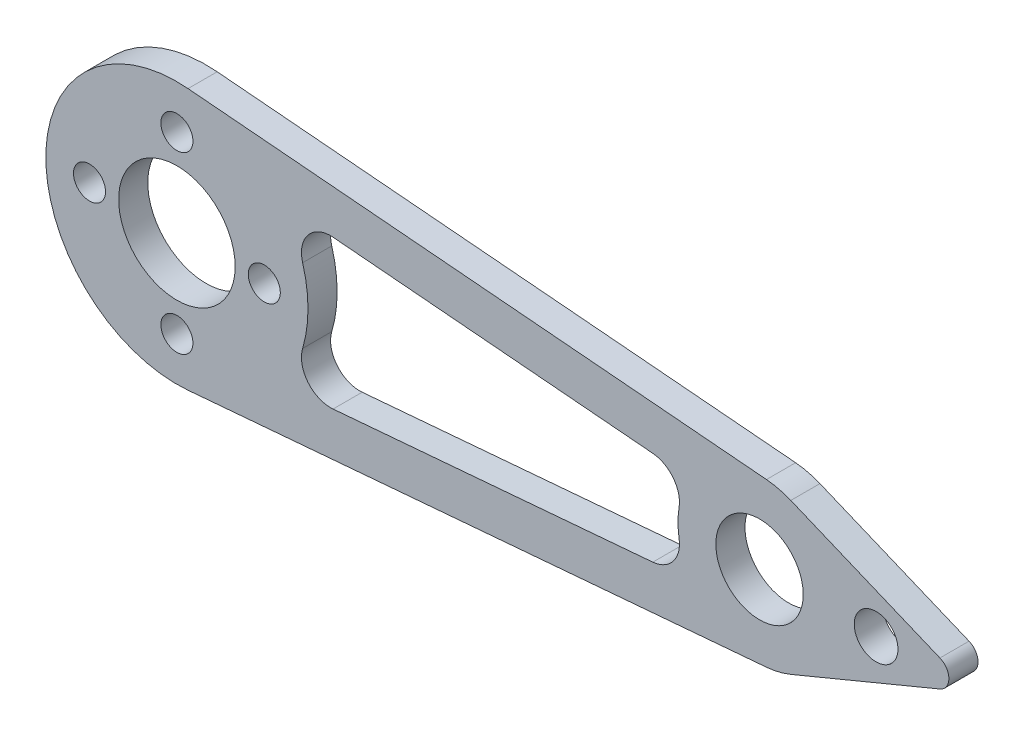
SolidWorks part; units mm, degrees
ref_plane "Plan de face" through (0, 0, 0) normal (0, 0, 1) x (1, 0, 0)
ref_plane "Plan de dessus" through (0, 0, 0) normal (0, 1, 0) x (1, 0, 0)
ref_plane "Plan de droite" through (0, 0, 0) normal (1, 0, 0) x (0, 0, -1)
sketch "Esquisse1" plane through (0, 0, 0) normal (0, 0, 1) x (1, 0, 0)
  circle A0 centre (0, 0) radius 6 construction
  circle A1 centre (0, 6) radius 1.1
  circle A2 centre (6, 0) radius 1.1
  circle A3 centre (0, -6) radius 1.1
  circle A4 centre (-6, 0) radius 1.1
  circle A5 centre (0, 0) radius 4
  circle A6 centre (0, 0) radius 9
  point P14 (0, 0)
  dimension "D1" = 12
  dimension "D2" = 2.2
  dimension "D4" = 2
  dimension "D5" = 3
  dimension "D3" = 4
extrude "Boss.-Extru.1" add sketch "Esquisse1" along normal blind 2
sketch "Esquisse2" plane through (0, 0, 2) normal (0, 0, 1) x (1, 0, 0)
  line L0 (0, 0) -> (40, 0) construction
  line L1 (0.765, 8.9674) -> (40.476, 5.5797)
  line L2 (0.765, -8.9674) -> (40.476, -5.5797)
  circle A0 centre (40, 0) radius 3
  arc A1 (40.476, -5.5797) -> (40.476, 5.5797) centre (40, 0) ccw
  circle A2 centre (0, 0) radius 9 construction
  arc A3 (0.765, -8.9674) -> (0.765, 8.9674) centre (0, 0) ccw
  dimension "D1" = 6
  dimension "D2" = 2.6
  dimension "D3" = 40
extrude "Boss.-Extru.2" add sketch "Esquisse2" against normal blind 2
sketch "Esquisse3" plane through (0, 0, 2) normal (0, 0, 1) x (1, 0, 0)
  line L0 (7.1939, 5.4081) -> (35.2791, 3.0122)
  line L1 (40.476, 5.5797) -> (0.765, 8.9674) construction
  line L2 (0, 0) -> (40, 0) construction
  line L3 (7.1939, -5.4081) -> (35.2791, -3.0122)
  arc A0 (7.1939, -5.4081) -> (7.1939, 5.4081) centre (0, 0) ccw
  arc A1 (35.2791, 3.0122) -> (35.2791, -3.0122) centre (40, 0) ccw
  dimension "D1" = 3
extrude "Enlèv. mat.-Extru.1" cut sketch "Esquisse3" against normal through all
fillet "Congé1" radius 2 4 edges at (35.2791, -3.0122, 1) (35.2791, 3.0122, 1) (7.1939, -5.4081, 1) (7.1939, 5.4081, 1)
sketch "Esquisse4" plane through (0, 0, 2) normal (0, 0, 1) x (1, 0, 0)
  line L0 (40, 0) -> (52, 0) construction
  line L1 (42.1467, 5.1722) -> (52.3833, 0.9236)
  line L2 (42.1467, -5.1722) -> (52.3833, -0.9236)
  arc A0 (40.476, -5.5797) -> (40.476, 5.5797) centre (40, 0) ccw construction
  arc A1 (42.1467, -5.1722) -> (42.1467, 5.1722) centre (40, 0) ccw
  arc A2 (52.3833, -0.9236) -> (52.3833, 0.9236) centre (52, 0) ccw
  circle A3 centre (48, 0) radius 1.5
  dimension "D1" = 2
  dimension "D3" = 3
  dimension "D2" = 12
  dimension "D4" = 8
extrude "Boss.-Extru.3" add sketch "Esquisse4" against normal blind 2
